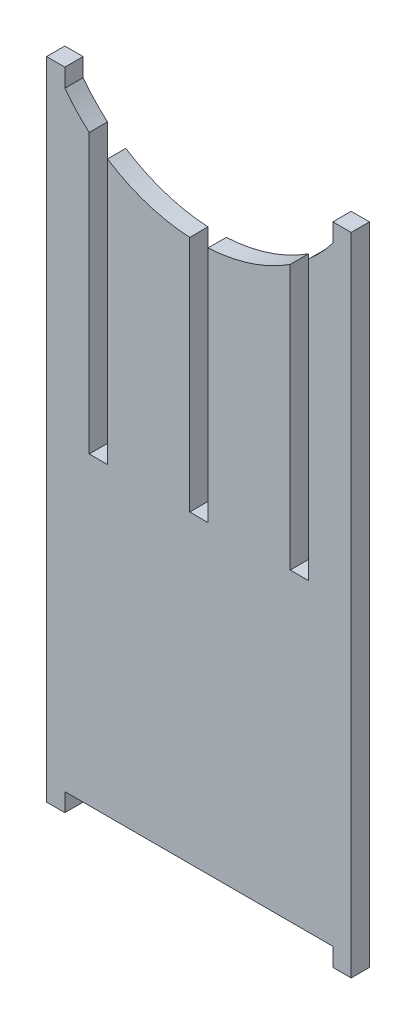
SolidWorks part; units mm, degrees
ref_plane "Front Plane" through (0, 0, 0) normal (0, 0, 1) x (1, 0, 0)
ref_plane "Top Plane" through (0, 0, 0) normal (0, 1, 0) x (1, 0, 0)
ref_plane "Right Plane" through (0, 0, 0) normal (1, 0, 0) x (0, 0, -1)
sketch "Esquisse1" plane through (0, 0, 0) normal (0, 0, 1) x (1, 0, 0)
  line L0 (-50, 0) -> (-50, 212)
  line L1 (-50, 212) -> (-44, 212)
  line L2 (-44, 212) -> (-44, 206)
  line L3 (-44, 206) -> (-36, 206)
  line L4 (-36, 206) -> (-36, 106)
  line L5 (-36, 106) -> (-30, 106)
  line L6 (-30, 106) -> (-30, 206)
  line L7 (-30, 206) -> (-3, 206)
  line L8 (-3, 206) -> (-3, 106)
  line L9 (-3, 106) -> (3, 106)
  line L10 (3, 106) -> (3, 206)
  line L11 (3, 206) -> (30, 206)
  line L12 (30, 206) -> (30, 106)
  line L13 (30, 106) -> (36, 106)
  line L14 (36, 106) -> (36, 206)
  line L15 (36, 206) -> (44, 206)
  line L16 (44, 206) -> (44, 212)
  line L17 (44, 212) -> (50, 212)
  line L18 (50, 212) -> (50, 0)
  line L19 (50, 0) -> (44, 0)
  line L20 (44, 0) -> (44, 6)
  line L21 (44, 6) -> (-44, 6)
  line L22 (-44, 6) -> (-44, 0)
  line L23 (-44, 0) -> (-50, 0)
  line L24 (0, 76.8909) -> (0, -17.439) construction
  point P27 (0, 106)
  dimension "D1" = 6
  dimension "D2" = 6
  dimension "D3" = 6
  dimension "D4" = 200
  dimension "D5" = 100
  dimension "D6" = 27
  dimension "D7" = 100
  dimension "D8" = 27
extrude "Boss.-Extru.1" add sketch "Esquisse1" along normal blind 6
sketch "Esquisse2" plane through (0, 0, 6) normal (0, 0, 1) x (1, 0, 0)
  line L1 (-44, 206) -> (44, 206)
  line L2 (-57.1095, 184) -> (77.0233, 184) construction
  arc A1 (-44, 206) -> (44, 206) centre (0, 239) ccw
  dimension "D1" = 22
extrude "Enlèv. mat.-Extru.1" cut sketch "Esquisse2" against normal blind 10
